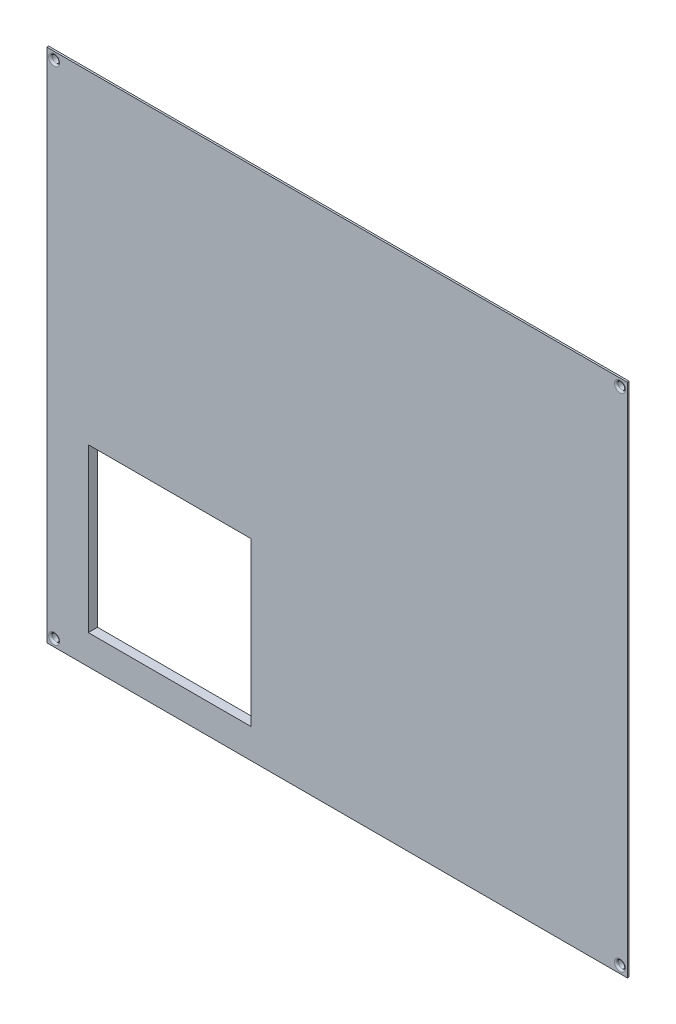
SolidWorks part; units mm, degrees
ref_plane "Front Plane" through (0, 0, 0) normal (0, 0, 1) x (1, 0, 0)
ref_plane "Top Plane" through (0, 0, 0) normal (0, 1, 0) x (1, 0, 0)
ref_plane "Right Plane" through (0, 0, 0) normal (1, 0, 0) x (0, 0, -1)
sketch "Sketch1" plane through (0, 0, 0) normal (0, 0, 1) x (1, 0, 0)
  line L1 (0, 0) -> (157, 0)
  line L2 (0, 0) -> (0, 139.5)
  line L3 (0, 139.5) -> (157, 139.5)
  line L4 (157, 0) -> (157, 139.5)
  dimension "D1" = 157
  dimension "D2" = 139.5
extrude "Boss-Extrude1" add sketch "Sketch1" along normal blind 2.5
chamfer "Chamfer1" distance 2 angle 45 4 edges at (78.5, 0, 0) (157, 69.75, 0) (78.5, 139.5, 0) (0, 69.75, 0)
sketch "Sketch5" plane through (0, 0, 0) normal (0, 0, -1) x (-1, 0, 0)
  line L0 (-2, 52) -> (-155, 52) construction
  line L1 (-2, 2) -> (-2, 137.5) construction
  line L2 (-155, 137.5) -> (-155, 2) construction
  line L3 (-155, 2) -> (-2, 2) construction
  line L5 (-11.224, 52) -> (-11.224, 2) construction
  line L7 (-55.224, 52) -> (-55.224, 2) construction
  line L8 (-55.224, 52) -> (-11.224, 52)
  line L9 (-55.224, 52) -> (-55.224, 8)
  line L10 (-55.224, 8) -> (-11.224, 8)
  line L11 (-11.224, 52) -> (-11.224, 8)
  point P18 (-101.4518, 55.6047)
  point P19 (-78.5, 20.9874)
  dimension "D1" = 50
  dimension "D2" = 44
extrude "Cut-Extrude1" cut sketch "Sketch5" against normal blind 10
sketch "Sketch6" plane through (0, 0, 2.5) normal (0, 0, 1) x (1, 0, 0)
  line L1 (2, 2) -> (155, 2) construction
  line L2 (2, 2) -> (2, 137.5) construction
  line L3 (2, 137.5) -> (155, 137.5) construction
  line L4 (155, 2) -> (155, 137.5) construction
  line L5 (0, 139.5) -> (0, 0) construction
  line L6 (0, 0) -> (157, 0) construction
  line L7 (157, 0) -> (157, 139.5) construction
  line L8 (157, 139.5) -> (0, 139.5) construction
  circle A0 centre (155, 137.5) radius 1
  circle A2 centre (2, 137.5) radius 1
  circle A3 centre (155, 2) radius 1
  circle A4 centre (2, 2) radius 1
  point P15 (0, 0)
  point P18 (0, 0)
  point P19 (154.7036, 2)
  point P21 (2, 1.9711)
  point P22 (0, 0)
  dimension "D5" = 2
  dimension "D1" = 2
  dimension "D2" = 2
  dimension "D3" = 2
  dimension "D4" = 2
extrude "Cut-Extrude2" cut sketch "Sketch6" against normal blind 10
fillet "Fillet1" radius 0.5 4 edges at (156, 2, 2.5) (3, 2, 2.5) (3, 137.5, 2.5) (156, 137.5, 2.5)
